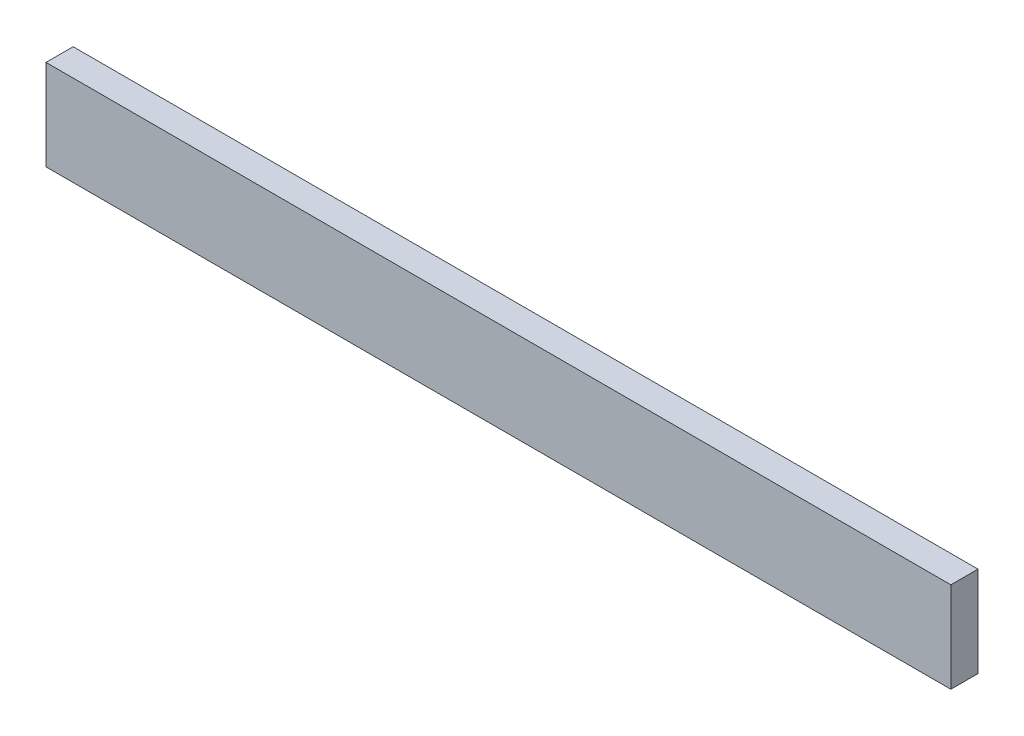
SolidWorks part; units mm, degrees
ref_plane "Přední rovina" through (0, 0, 0) normal (0, 0, 1) x (1, 0, 0)
ref_plane "Horní rovina" through (0, 0, 0) normal (0, 1, 0) x (1, 0, 0)
ref_plane "Pravá rovina" through (0, 0, 0) normal (1, 0, 0) x (0, 0, -1)
sketch "Sketch1" plane through (0, 0, 0) normal (0, 0, 1) x (1, 0, 0)
  line L1 (0, 0) -> (100, 0)
  line L2 (0, 0) -> (0, 10)
  line L3 (0, 10) -> (100, 10)
  line L4 (100, 0) -> (100, 10)
  dimension "D1" = 100
  dimension "D2" = 10
extrude "Boss-Extrude1" add sketch "Sketch1" along normal blind 3
